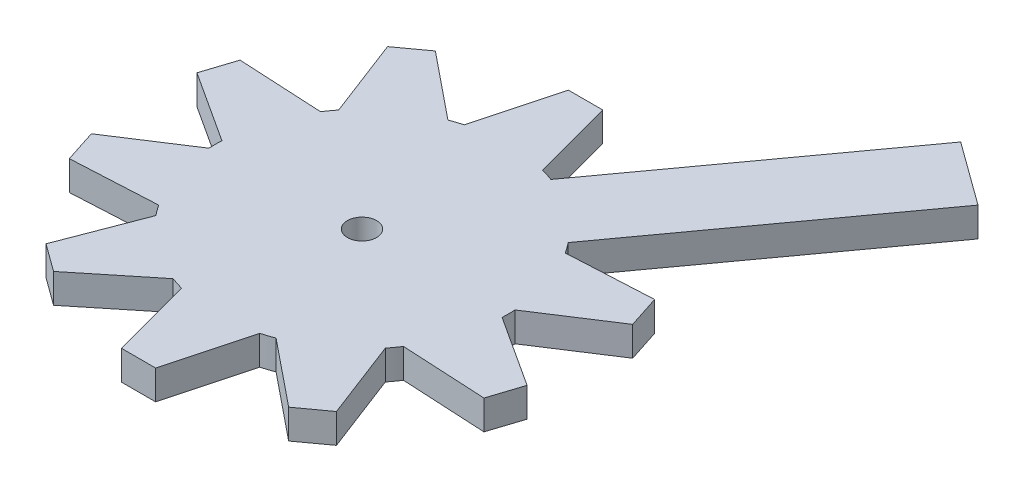
SolidWorks part; units mm, degrees
ref_plane "Front Plane" through (0, 0, 0) normal (0, 0, 1) x (1, 0, 0)
ref_plane "Top Plane" through (0, 0, 0) normal (0, 1, 0) x (1, 0, 0)
ref_plane "Right Plane" through (0, 0, 0) normal (1, 0, 0) x (0, 0, -1)
sketch "Sketch1" plane through (0, 0, 0) normal (0, 1, 0) x (1, 0, 0)
  circle A0 centre (0, 0) radius 15
  dimension "D1" = 30
extrude "Boss-Extrude1" add sketch "Sketch1" along normal blind 3
sketch "Sketch2" plane through (0, 3, 0) normal (0, 1, 0) x (1, 0, 0)
  line L0 (0, 0) -> (0, -26.5201) construction
  line L1 (1.75, -22.8539) -> (-1.75, -22.8539)
  line L2 (-1.75, -22.8539) -> (-4, -14.4568)
  line L3 (-4, -14.4568) -> (4, -14.4568)
  line L4 (4, -14.4568) -> (1.75, -22.8539)
  line L5 (-14.849, -17.4606) -> (-11.7336, -9.3447)
  line L6 (-11.7336, -9.3447) -> (-5.2614, -14.047)
  line L7 (-5.2614, -14.047) -> (-12.0174, -19.5179)
  line L8 (-12.0174, -19.5179) -> (-14.849, -17.4606)
  line L9 (-22.2762, -5.3979) -> (-14.9853, -0.6632)
  line L10 (-14.9853, -0.6632) -> (-12.5132, -8.2716)
  line L11 (-12.5132, -8.2716) -> (-21.1946, -8.7266)
  line L12 (-21.1946, -8.7266) -> (-22.2762, -5.3979)
  line L13 (-21.1946, 8.7266) -> (-12.5132, 8.2716)
  line L14 (-12.5132, 8.2716) -> (-14.9853, 0.6632)
  line L15 (-14.9853, 0.6632) -> (-22.2762, 5.3979)
  line L16 (-22.2762, 5.3979) -> (-21.1946, 8.7266)
  line L17 (-12.0174, 19.5179) -> (-5.2614, 14.047)
  line L18 (-5.2614, 14.047) -> (-11.7336, 9.3447)
  line L19 (-11.7336, 9.3447) -> (-14.849, 17.4606)
  line L20 (-14.849, 17.4606) -> (-12.0174, 19.5179)
  line L21 (1.75, 22.8539) -> (4, 14.4568)
  line L22 (4, 14.4568) -> (-4, 14.4568)
  line L23 (-4, 14.4568) -> (-1.75, 22.8539)
  line L24 (-1.75, 22.8539) -> (1.75, 22.8539)
  line L25 (14.849, 17.4606) -> (11.7336, 9.3447)
  line L26 (11.7336, 9.3447) -> (5.2614, 14.047)
  line L27 (5.2614, 14.047) -> (12.0174, 19.5179)
  line L28 (12.0174, 19.5179) -> (14.849, 17.4606)
  line L29 (22.2762, 5.3979) -> (14.9853, 0.6632)
  line L30 (14.9853, 0.6632) -> (12.5132, 8.2716)
  line L31 (12.5132, 8.2716) -> (21.1946, 8.7266)
  line L32 (21.1946, 8.7266) -> (22.2762, 5.3979)
  line L33 (21.1946, -8.7266) -> (12.5132, -8.2716)
  line L34 (12.5132, -8.2716) -> (14.9853, -0.6632)
  line L35 (14.9853, -0.6632) -> (22.2762, -5.3979)
  line L36 (22.2762, -5.3979) -> (21.1946, -8.7266)
  line L37 (12.0174, -19.5179) -> (5.2614, -14.047)
  line L38 (5.2614, -14.047) -> (11.7336, -9.3447)
  line L39 (11.7336, -9.3447) -> (14.849, -17.4606)
  line L40 (14.849, -17.4606) -> (12.0174, -19.5179)
  line L41 (0, 0) -> (4, -14.4568) construction
  circle A0 centre (0, 0) radius 15 construction
  point P6 (0, -22.8539)
  dimension "D1" = 8
  dimension "D2" = 3.5
  dimension "D3" = 75
  dimension "D4" = 10
  dimension "D5" = 15
extrude "Boss-Extrude4" add sketch "Sketch2" against normal blind 3
sketch "Sketch3" plane through (0, 3, 0) normal (0, 1, 0) x (1, 0, 0)
  line L0 (0, 0) -> (5.2614, 14.047)
  line L1 (0, 0) -> (11.7336, 9.3447)
  line L3 (5.2614, 14.047) -> (22.895, 38.3175)
  line L4 (11.7336, 9.3447) -> (29.3671, 33.6152)
  line L5 (22.895, 38.3175) -> (29.3671, 33.6152)
  dimension "D1" = 30
  dimension "D2" = 8
  dimension "D3" = 30
extrude "Boss-Extrude5" add sketch "Sketch3" against normal blind 3
sketch "Sketch4" plane through (0, 3, 0) normal (0, 1, 0) x (1, 0, 0)
  circle A0 centre (0, 0) radius 1.5
  dimension "D1" = 3
extrude "Cut-Extrude1" cut sketch "Sketch4" against normal blind 3
